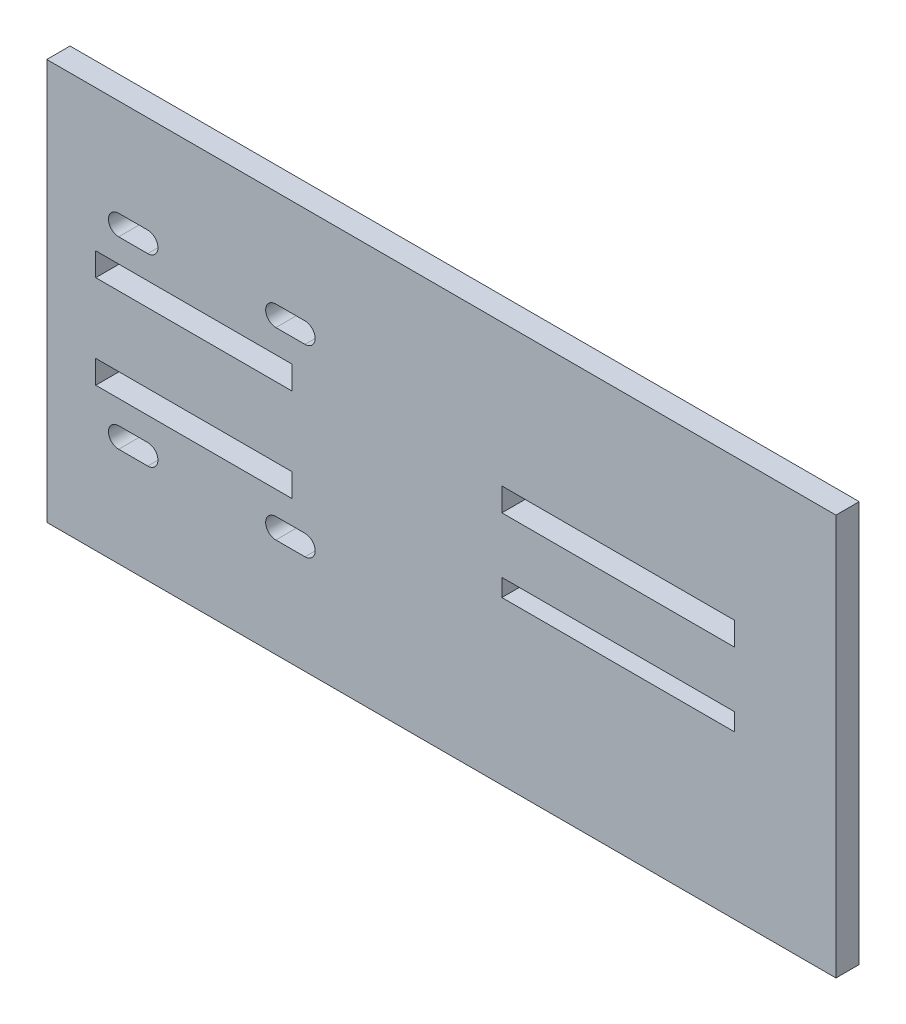
SolidWorks part; units mm, degrees
ref_plane "前视基准面" through (0, 0, 0) normal (0, 0, 1) x (1, 0, 0)
ref_plane "上视基准面" through (0, 0, 0) normal (0, 1, 0) x (1, 0, 0)
ref_plane "右视基准面" through (0, 0, 0) normal (1, 0, 0) x (0, 0, -1)
sketch "草图1" plane through (0, 0, 0) normal (0, 0, 1) x (1, 0, 0)
  line L0 (3.0082, 28.3353) -> (43.0082, 28.3353) construction
  line L1 (-5.3398, 46.7921) -> (130.2145, 46.7921)
  line L2 (-5.3398, 46.7921) -> (-5.3398, -22.065)
  line L3 (-5.3398, -22.065) -> (130.2145, -22.065)
  line L4 (130.2145, 46.7921) -> (130.2145, -22.065)
  line L5 (7.0082, 30.0853) -> (12.0082, 30.0853)
  line L6 (7.0082, 26.5853) -> (12.0082, 26.5853)
  line L7 (23.0082, 28.3353) -> (23.0082, -3.2647) construction
  line L8 (39.0082, 26.5853) -> (34.0082, 26.5853)
  line L9 (39.0082, 30.0853) -> (34.0082, 30.0853)
  line L10 (23.0082, 12.5353) -> (54.7234, 12.5353) construction
  line L11 (7.0082, -1.5147) -> (12.0082, -1.5147)
  line L12 (7.0082, -5.0147) -> (12.0082, -5.0147)
  line L13 (3.0693, 18.5353) -> (36.8182, 18.5353)
  line L14 (39.0082, -5.0147) -> (34.0082, -5.0147)
  line L15 (39.0082, -1.5147) -> (34.0082, -1.5147)
  line L16 (23.0082, 28.3353) -> (45.0417, 28.3353) construction
  line L17 (23.0082, -3.2647) -> (45.0417, -3.2647) construction
  line L18 (3.0693, 6.5353) -> (36.8182, 6.5353)
  line L19 (3.0693, 6.5353) -> (3.0693, 2.5353)
  line L20 (3.0693, 22.5353) -> (36.8182, 22.5353)
  line L21 (3.0693, 22.5353) -> (3.0693, 18.5353)
  line L22 (48.2051, 12.5353) -> (48.2051, 18.4353) construction
  line L23 (3.0693, 2.5353) -> (36.8182, 2.5353)
  line L24 (48.2051, 12.5353) -> (48.2051, 8.8353) construction
  line L25 (36.8182, 18.5353) -> (36.8182, 22.5353)
  line L26 (36.8182, 6.5353) -> (36.8182, 2.5353)
  line L27 (48.2051, 18.4353) -> (74.6476, 18.4353) construction
  line L28 (74.6476, 18.4353) -> (74.6476, 22.4353) construction
  line L29 (74.6476, 22.4353) -> (48.2051, 22.4353) construction
  line L30 (48.2051, 22.4353) -> (48.2051, 18.4353) construction
  line L31 (48.2051, 8.8353) -> (74.6476, 8.8353) construction
  line L32 (74.6476, 8.8353) -> (74.6476, 5.8353) construction
  line L33 (48.2051, 8.8353) -> (48.2051, 5.8353) construction
  line L34 (48.2051, 5.8353) -> (74.6476, 5.8353) construction
  line L35 (43.0082, -22.065) -> (3.0082, -22.065) construction
  line L36 (3.0082, -22.065) -> (3.0082, -27.065) construction
  line L37 (3.0082, -27.065) -> (14.5082, -27.065) construction
  line L38 (14.5082, -27.065) -> (14.5082, -44.065) construction
  line L39 (14.5082, -44.065) -> (21.5082, -44.065) construction
  line L40 (21.5082, -44.065) -> (21.5082, -37.8745) construction
  line L41 (24.5082, -44.065) -> (24.5082, -37.8745) construction
  line L42 (31.5082, -44.065) -> (24.5082, -44.065) construction
  line L43 (31.5082, -27.065) -> (31.5082, -44.065) construction
  line L44 (43.0082, -27.065) -> (31.5082, -27.065) construction
  line L45 (43.0082, -22.065) -> (43.0082, -27.065) construction
  line L46 (23.0082, -3.2647) -> (23.0082, -22.065) construction
  line L47 (92.8294, -37.065) -> (72.8294, -37.065) construction
  line L48 (72.8294, -37.065) -> (72.8294, 5.8353) construction
  line L49 (72.8294, 5.8353) -> (112.8294, 5.8353) construction
  line L50 (72.8294, 8.8353) -> (72.8294, 18.4353) construction
  line L51 (72.8294, 22.4353) -> (112.8294, 22.4353) construction
  line L52 (72.8294, 18.4353) -> (72.8294, 22.4353) construction
  line L53 (72.8294, 5.8353) -> (72.8294, 8.8353) construction
  line L54 (72.8294, 8.8353) -> (112.8294, 8.8353) construction
  line L55 (72.8294, 18.4353) -> (112.8294, 18.4353) construction
  line L56 (92.8294, 22.4353) -> (92.8294, -37.065) construction
  line L57 (112.8294, 5.8353) -> (112.8294, 8.8353) construction
  line L58 (112.8294, 18.4353) -> (112.8294, 22.4353) construction
  line L59 (72.8294, 22.4353) -> (72.8294, 18.4353)
  line L60 (72.8294, 18.4353) -> (112.8294, 18.4353)
  line L61 (112.8294, 18.4353) -> (112.8294, 22.4353)
  line L62 (112.8294, 22.4353) -> (72.8294, 22.4353)
  line L63 (72.8294, 8.8353) -> (112.8294, 8.8353)
  line L64 (112.8294, 8.8353) -> (112.8294, 5.8353)
  line L65 (112.8294, 5.8353) -> (72.8294, 5.8353)
  line L66 (72.8294, 5.8353) -> (72.8294, 8.8353)
  arc A0 (12.0082, 26.5853) -> (12.0082, 30.0853) centre (12.0082, 28.3353) ccw
  arc A1 (7.0082, 30.0853) -> (7.0082, 26.5853) centre (7.0082, 28.3353) ccw
  arc A2 (39.0082, 30.0853) -> (39.0082, 26.5853) centre (39.0082, 28.3353) cw
  arc A3 (34.0082, 26.5853) -> (34.0082, 30.0853) centre (34.0082, 28.3353) cw
  arc A4 (7.0082, -5.0147) -> (7.0082, -1.5147) centre (7.0082, -3.2647) cw
  arc A5 (12.0082, -1.5147) -> (12.0082, -5.0147) centre (12.0082, -3.2647) cw
  arc A6 (39.0082, -1.5147) -> (39.0082, -5.0147) centre (39.0082, -3.2647) cw
  arc A7 (34.0082, -5.0147) -> (34.0082, -1.5147) centre (34.0082, -3.2647) cw
  arc A8 (24.5082, -37.8745) -> (21.5082, -37.8745) centre (23.0082, -32.065) ccw construction
  circle A9 centre (23.0082, -32.065) radius 70 construction
  circle A10 centre (92.8294, -37.065) radius 12.2 construction
  point P6 (23.0082, 28.3353)
  point P7 (12.0082, 28.3353)
  point P9 (23.0082, 12.5353)
  point P10 (7.0082, 28.3353)
  point P24 (23.0082, 18.5353)
  point P25 (23.0082, -3.2647)
  point P28 (23.0082, 6.5353)
  point P31 (3.0693, 18.5353)
  point P50 (23.0082, 6.5353)
  point P51 (23.0082, 18.5353)
  point P55 (36.8182, 12.5353)
  point P68 (23.0082, -22.065)
  point P71 (14.5082, -44.065)
  point P75 (21.5082, -44.065)
  point P82 (23.0082, -22.065)
  point P95 (92.8294, 8.8353)
  point P96 (92.8294, 5.8353)
  point P97 (92.8294, 18.4353)
  dimension "D11" = 6
  dimension "D12" = 15
  dimension "D1" = 11
  dimension "D2" = 5
  dimension "D3" = 6
  dimension "D4" = 4
  dimension "D5" = 31.6
  dimension "D6" = 4
  dimension "D7" = 13.81
  dimension "D8" = 5.9
  dimension "D9" = 3.7
  dimension "D10" = 4
extrude "凸台-拉伸1" add sketch "草图1" along normal blind 4
